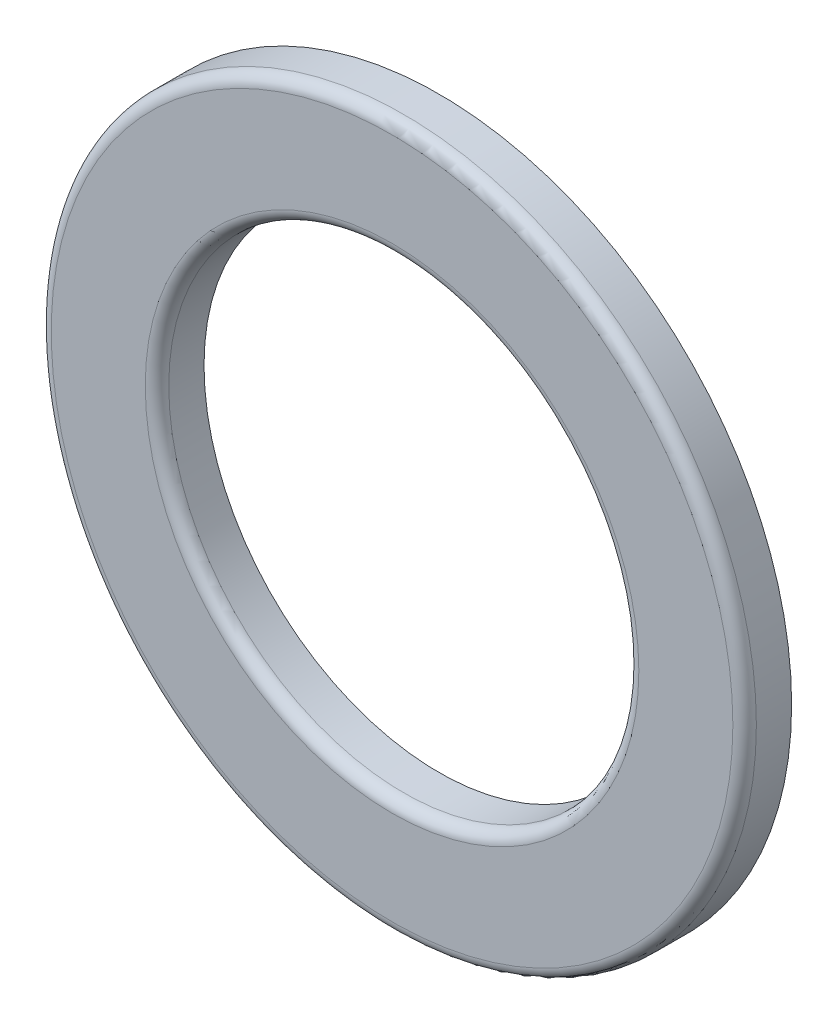
SolidWorks part; units mm, degrees
material "AISI 1020 Steel, Cold Rolled"
ref_plane "Front Plane" through (0, 0, 0) normal (0, 0, 1) x (1, 0, 0)
ref_plane "Top Plane" through (0, 0, 0) normal (0, 1, 0) x (1, 0, 0)
ref_plane "Right Plane" through (0, 0, 0) normal (1, 0, 0) x (0, 0, -1)
sketch "Sketch1" plane through (0, 0, 0) normal (0, 0, 1) x (1, 0, 0)
  circle A0 centre (0, 0) radius 15
  circle A1 centre (0, 0) radius 10
  dimension "D1" = 20
  dimension "D2" = 30
extrude "Boss-Extrude1" add sketch "Sketch1" along normal blind 2
fillet "Fillet1" radius 0.5 2 edges at (10, 0, 2) (15, 0, 2)
